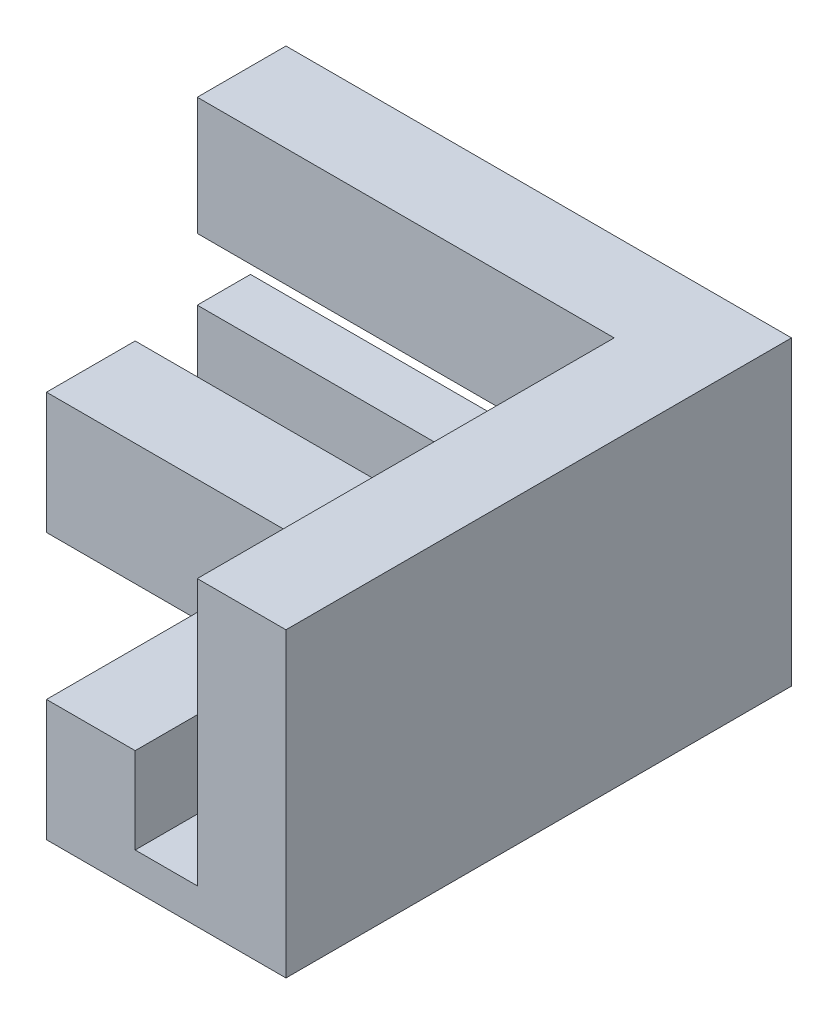
SolidWorks part; units mm, degrees
ref_plane "Front Plane" through (0, 0, 0) normal (0, 0, 1) x (1, 0, 0)
ref_plane "Top Plane" through (0, 0, 0) normal (0, 1, 0) x (1, 0, 0)
ref_plane "Right Plane" through (0, 0, 0) normal (1, 0, 0) x (0, 0, -1)
sketch "Sketch1" plane through (0, 0, 0) normal (0, 1, 0) x (1, 0, 0)
  line L0 (0, 4.3917) -> (0, 0.8917)
  line L1 (0, 0.8917) -> (15, 0.8917)
  line L2 (15, 0.8917) -> (15, -14.1083)
  line L3 (15, -14.1083) -> (18.5, -14.1083)
  line L4 (18.5, -14.1083) -> (18.5, 4.3917)
  line L5 (18.5, 4.3917) -> (0, 4.3917)
  line L6 (23.5, 9.3917) -> (-5, 9.3917)
  line L7 (-5, 9.3917) -> (-5, -4.1083)
  line L8 (-5, -4.1083) -> (10, -4.1083)
  line L9 (10, -4.1083) -> (10, -19.1083)
  line L10 (10, -19.1083) -> (23.5, -19.1083)
  line L11 (23.5, -19.1083) -> (23.5, 9.3917)
  point P3 (18.5, 4.3917)
  dimension "D1" = 3.5
  dimension "D2" = 3.5
  dimension "D3" = 15
  dimension "D4" = 15
  dimension "D5" = 5
extrude "Boss-Extrude1" add sketch "Sketch1" along normal blind 15
sketch "Sketch2" plane through (0, 0, 0) normal (0, -1, 0) x (1, 0, 0)
  line L0 (-5, 4.1083) -> (10, 4.1083)
  line L1 (10, 4.1083) -> (10, 19.1083)
  line L2 (10, 19.1083) -> (23.5, 19.1083)
  line L3 (23.5, 19.1083) -> (23.5, -9.3917)
  line L4 (23.5, -9.3917) -> (-5, -9.3917)
  line L5 (-5, -9.3917) -> (-5, 4.1083)
extrude "Boss-Extrude2" add sketch "Sketch2" along normal blind 2
sketch "Sketch3" plane through (0, 15, 0) normal (0, 1, 0) x (1, 0, 0)
  line L0 (18.5, 4.3917) -> (-5, 4.3917)
  line L1 (-5, 9.3917) -> (-5, -4.1083) construction
  line L2 (-5, 4.3917) -> (-5, 0.8917)
  line L5 (15, -19.1083) -> (18.5, -19.1083)
  line L6 (18.5, -19.1083) -> (18.5, 4.3917)
  line L7 (18.5, -14.1083) -> (18.5, 4.3917) construction
  line L9 (10, -19.1083) -> (23.5, -19.1083) construction
  line L10 (-5, 0.8917) -> (-5, -4.1083)
  line L11 (-5, -4.1083) -> (10, -4.1083)
  line L12 (10, -4.1083) -> (10, -19.1083)
  line L13 (10, -19.1083) -> (15, -19.1083)
extrude "Cut-Extrude1" cut sketch "Sketch3" against normal offset from surface (10.15 mm away) 4.85 up to face at (11.1667, 0, 2.9416)
sketch "Sketch4" plane through (0, 4.85, 0) normal (0, 1, 0) x (1, 0, 0)
  line L0 (-5, 4.3917) -> (18.5, 4.3917)
  line L1 (18.5, 4.3917) -> (18.5, -19.1083)
  line L2 (18.5, -19.1083) -> (15, -19.1083)
  line L3 (18.5, -19.1083) -> (10, -19.1083) construction
  line L4 (15, -19.1083) -> (15, 0.8917)
  line L5 (15, 0.8917) -> (-5, 0.8917)
  line L6 (-5, 0.8917) -> (-5, 4.3917)
  line L7 (0, 0.8917) -> (15, 0.8917) construction
  line L8 (15, 0.8917) -> (15, -14.1083) construction
extrude "Cut-Extrude2" cut sketch "Sketch4" against normal up to surface (4.85 mm away) up to face at (11.1667, 0, 2.9416)
sketch "Sketch5" plane through (0, 0, -4.3917) normal (0, 0, 1) x (1, 0, 0)
  line L0 (-5, 4.85) -> (18.5, 4.85)
  line L1 (18.5, 15) -> (18.5, 0) construction
  line L2 (18.5, 4.85) -> (18.5, 8.35)
  line L3 (18.5, 8.35) -> (-10.7412, 8.35)
  line L4 (-10.7412, 8.35) -> (-10.7412, 4.85)
  line L5 (-10.7412, 4.85) -> (-5, 4.85)
  dimension "D1" = 3.5
extrude "Cut-Extrude5" cut sketch "Sketch5" against normal through all both and the other way through all
chamfer "Chamfer3" distance 2 angle 45 2 edges at (6.75, 4.85, -9.3917) (6.75, 8.35, -9.3917)
